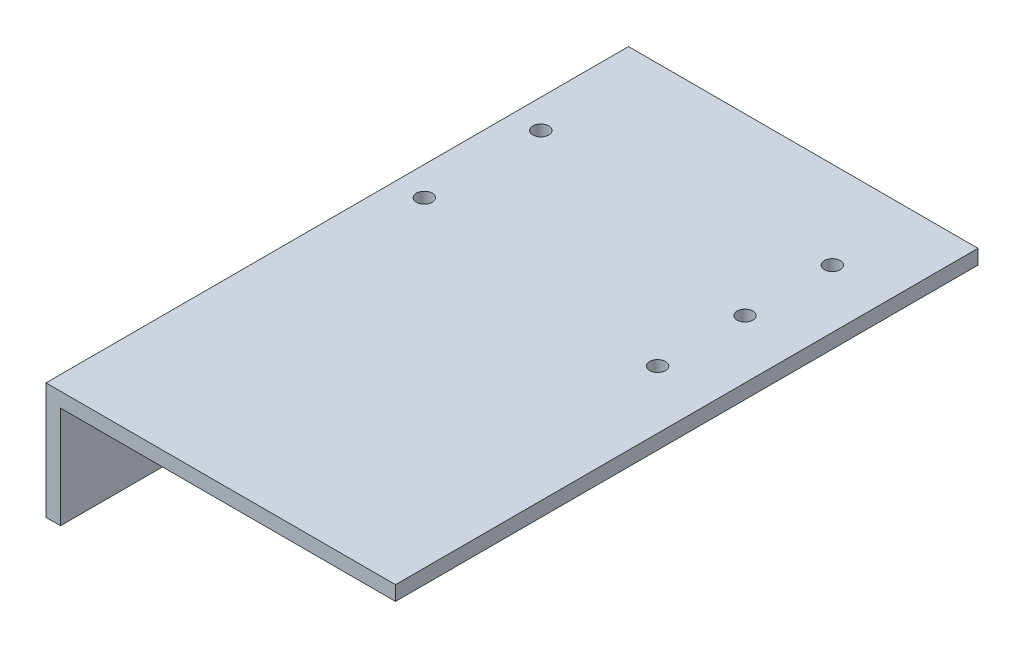
SolidWorks part; units mm, degrees
ref_plane "Front Plane" through (0, 0, 0) normal (0, 0, 1) x (1, 0, 0)
ref_plane "Top Plane" through (0, 0, 0) normal (0, 1, 0) x (1, 0, 0)
ref_plane "Right Plane" through (0, 0, 0) normal (1, 0, 0) x (0, 0, -1)
sketch "Sketch2" plane through (0, 0, 0) normal (0, 0, 1) x (1, 0, 0)
  line L0 (0, 0) -> (-76.2, 0)
  line L1 (-76.2, 0) -> (-76.2, -25.4)
  line L2 (-76.2, -25.4) -> (-73.025, -25.4)
  line L3 (-73.025, -25.4) -> (-73.025, -3.175)
  line L4 (-73.025, -3.175) -> (0, -3.175)
  line L5 (0, -3.175) -> (0, 0)
  dimension "D1" = 76.2
  dimension "D2" = 25.4
  dimension "D3" = 3.175
  dimension "D4" = 3.175
extrude "Boss-Extrude1" add sketch "Sketch2" along normal blind 76.2
hole_wizard "Tap Drill for #6-32 Tap1" positions "Sketch4" profile "Sketch3" hole size "#6-32" standard "ANSI Inch" end condition through all
sketch "Sketch4" plane through (-76.2, 0, 0) normal (-1, 0, 0) x (0, 0, 1)
  line L2 (76.2, 0) -> (0, 0) construction
  line L4 (12.7, 0) -> (12.7, -15.24) construction
  line L5 (12.7, -15.24) -> (25.4, -15.24) construction
  line L7 (76.2, 0) -> (25.4, 0) construction
  line L8 (25.4, 0) -> (25.4, -15.24) construction
  point P0 (25.4, -15.24)
  point P2 (12.7, -15.24)
  dimension "D1" = 15.24
  dimension "D2" = 12.7
  dimension "D3" = 12.7
sketch "Sketch3" plane through (-76.2, -15.24, 25.4) normal (0, 1, 0) x (0, 0, 1)
  line L0 (0, 0) -> (0, 76.2)
  line L1 (0, 76.2) -> (1.3525, 76.2)
  line L2 (1.3525, 76.2) -> (1.3525, 0)
  line L5 (1.3525, 0) -> (0, 0)
  line L11 (0, -6.35) -> (0, 107.95) construction
  dimension "Thru Hole Dia." = 2.7051
  dimension "Thru Hole Depth" = 76.2
hole_wizard "Tap Drill for #8-32 Tap1" positions "Sketch6" profile "Sketch5" hole size "#8-32" standard "ANSI Inch" end condition through all
sketch "Sketch6" plane through (0, 0, 0) normal (0, 1, 0) x (1, 0, 0)
  line L0 (-76.2, 0) -> (-69.9177, 0) construction
  line L1 (0, 0) -> (-76.2, 0) construction
  line L2 (0, -76.2) -> (-76.2, -76.2) construction
  point P0 (-69.9177, -25.4)
  point P2 (-69.9177, -50.8)
  dimension "D1" = 6.2823
  dimension "D2" = 25.4
  dimension "D3" = 25.4
sketch "Sketch5" plane through (-69.9177, 0, 25.4) normal (1, 0, 0) x (0, 0, 1)
  line L0 (0, 0) -> (0, 25.4)
  line L1 (0, 25.4) -> (1.7272, 25.4)
  line L2 (1.7272, 25.4) -> (1.7272, 0)
  line L5 (1.7272, 0) -> (0, 0)
  line L11 (0, -6.35) -> (0, 107.95) construction
  dimension "Thru Hole Dia." = 3.4544
  dimension "Thru Hole Depth" = 25.4
sketch "Sketch8" plane through (-76.2, 0, 0) normal (-1, 0, 0) x (0, 0, 1)
  line L1 (76.2, 0) -> (76.2, -25.4) construction
  line L2 (76.2, -15.24) -> (38.1, -15.24) construction
  line L3 (36.449, -16.891) -> (39.751, -16.891)
  line L4 (36.449, -16.891) -> (36.449, -13.589)
  line L5 (36.449, -13.589) -> (39.751, -13.589)
  line L6 (39.751, -16.891) -> (39.751, -13.589)
  line L7 (36.449, -16.891) -> (39.751, -13.589) construction
  line L8 (36.449, -13.589) -> (39.751, -16.891) construction
  dimension "D1" = 38.1
  dimension "D2" = 3.302
  dimension "D3" = 3.302
extrude "Cut-Extrude1" cut sketch "Sketch8" against normal up to next
hole_wizard "Tap Drill for #8-32 Tap2" positions "Sketch10" profile "Sketch9" hole size "#8-32" standard "ANSI Inch" end condition through all
sketch "Sketch10" plane through (0, 0, 0) normal (0, 1, 0) x (1, 0, 0)
  line L4 (0, -76.2) -> (0, 0) construction
  line L5 (0, 0) -> (-76.2, 0) construction
  point P0 (-12.7, -19.05)
  point P2 (-12.7, -38.1)
  point P4 (-12.7, -57.15)
  dimension "D1" = 19.05
  dimension "D2" = 19.05
  dimension "D3" = 12.7
  dimension "D4" = 19.05
sketch "Sketch9" plane through (-12.7, 0, 19.05) normal (1, 0, 0) x (0, 0, 1)
  line L0 (0, 0) -> (0, 25.4)
  line L1 (0, 25.4) -> (1.7272, 25.4)
  line L2 (1.7272, 25.4) -> (1.7272, 0)
  line L5 (1.7272, 0) -> (0, 0)
  line L11 (0, -6.35) -> (0, 107.95) construction
  dimension "Thru Hole Dia." = 3.4544
  dimension "Thru Hole Depth" = 25.4
sketch "Sketch11" plane through (0, 0, 76.2) normal (0, 0, 1) x (1, 0, 0)
  line L0 (-76.2, 0) -> (-76.2, -25.4)
  line L1 (-76.2, -25.4) -> (-73.025, -25.4)
  line L2 (-73.025, -25.4) -> (-73.025, -3.175)
  line L3 (-73.025, -3.175) -> (0, -3.175)
  line L4 (0, -3.175) -> (0, 0)
  line L5 (0, 0) -> (-76.2, 0)
extrude "Boss-Extrude2" add sketch "Sketch11" along normal blind 50.8
